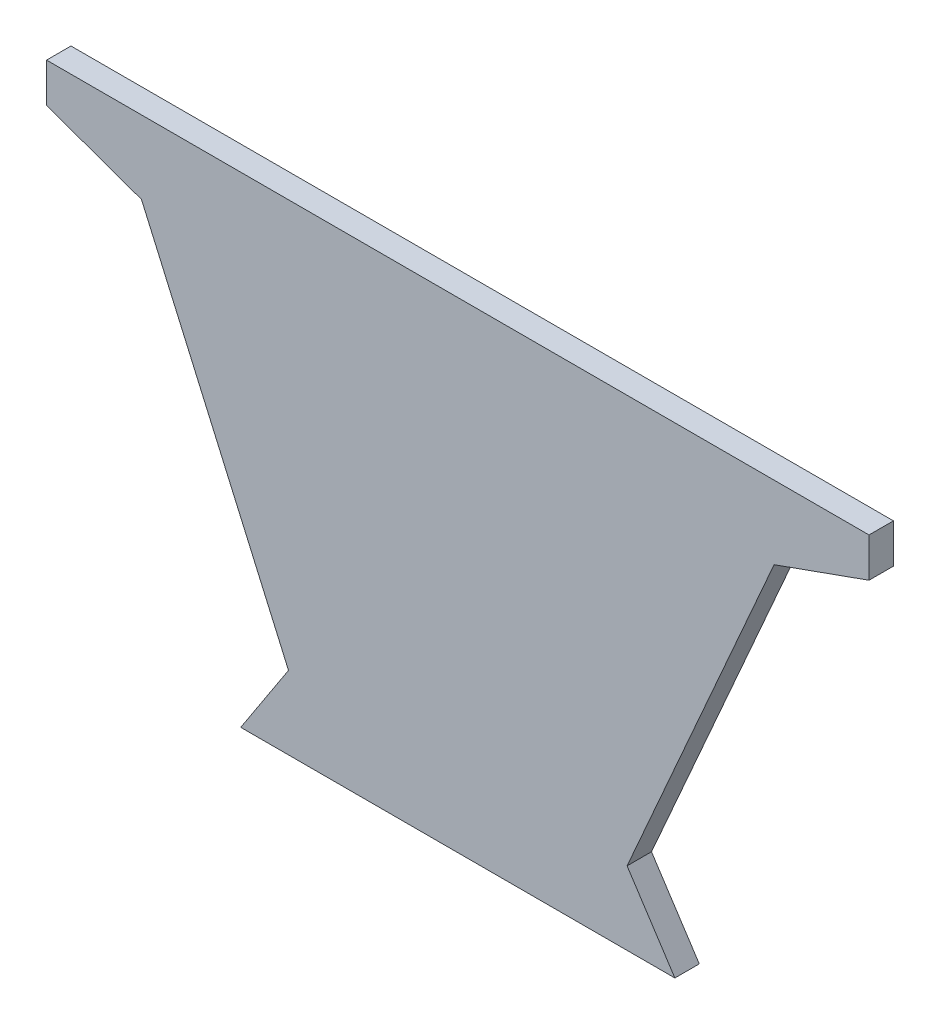
SolidWorks part; units mm, degrees
ref_plane "Front Plane" through (0, 0, 0) normal (0, 0, 1) x (1, 0, 0)
ref_plane "Top Plane" through (0, 0, 0) normal (0, 1, 0) x (1, 0, 0)
ref_plane "Right Plane" through (0, 0, 0) normal (1, 0, 0) x (0, 0, -1)
sketch "Sketch1" plane through (0, 0, 0) normal (0, 0, 1) x (1, 0, 0)
  line L0 (-44.9631, -50) -> (44.9631, -50)
  line L1 (44.9631, -50) -> (85, 41.0508)
  line L2 (85, 41.0508) -> (85, 50)
  line L3 (85, 50) -> (-85, 50)
  line L6 (-85, 50) -> (-85, 41.0508)
  line L7 (-85, 41.0508) -> (-44.9631, -50)
  line L8 (-84.25, 41.2084) -> (-44.4735, -49.25)
  line L9 (-44.4735, -49.25) -> (44.4735, -49.25)
  line L10 (44.4735, -49.25) -> (84.25, 41.2084)
  line L11 (84.25, 41.2084) -> (84.25, 49.25)
  line L12 (84.25, 49.25) -> (-84.25, 49.25)
  line L13 (-84.25, 49.25) -> (-84.25, 41.2084)
  dimension "D1" = 0.75
extrude "Boss-Extrude1" add sketch "Sketch1" along normal blind 5 contours L8 L9 L10 L11 L12 L13
sketch "Sketch2" plane through (0, 0, 0) normal (0, 0, -1) x (-1, 0, 0)
  line L6 (-34.6832, -34.25) -> (-44.4735, -49.25)
  line L7 (-44.4735, -49.25) -> (-84.25, 41.2084)
  line L8 (-84.25, 41.2084) -> (-64.8041, 34.25)
  line L9 (64.8041, 34.25) -> (84.25, 41.2084)
  line L10 (84.25, 41.2084) -> (44.4735, -49.25) construction
  line L11 (84.25, 41.2084) -> (44.4735, -49.25)
  line L12 (64.8041, 34.25) -> (-64.8041, 34.25)
  line L13 (-64.8041, 34.25) -> (-34.6832, -34.25)
  line L14 (-34.6832, -34.25) -> (34.6832, -34.25)
  line L15 (34.6832, -34.25) -> (64.8041, 34.25)
  line L16 (64.8041, 34.25) -> (-64.8041, 34.25)
  line L17 (-64.8041, 34.25) -> (-34.6832, -34.25)
  line L18 (-34.6832, -34.25) -> (34.6832, -34.25)
  line L19 (34.6832, -34.25) -> (64.8041, 34.25)
  line L20 (44.4735, -49.25) -> (34.6832, -34.25)
  line M8 (-84.25, 41.2084) -> (-44.4735, -49.25)
  line M10 (44.4735, -49.25) -> (84.25, 41.2084)
  dimension "D1" = 15
extrude "Cut-Extrude1" cut sketch "Sketch2" against normal blind 10 contours L20 L9 L19 M10 | L17 L8 L6 M8
